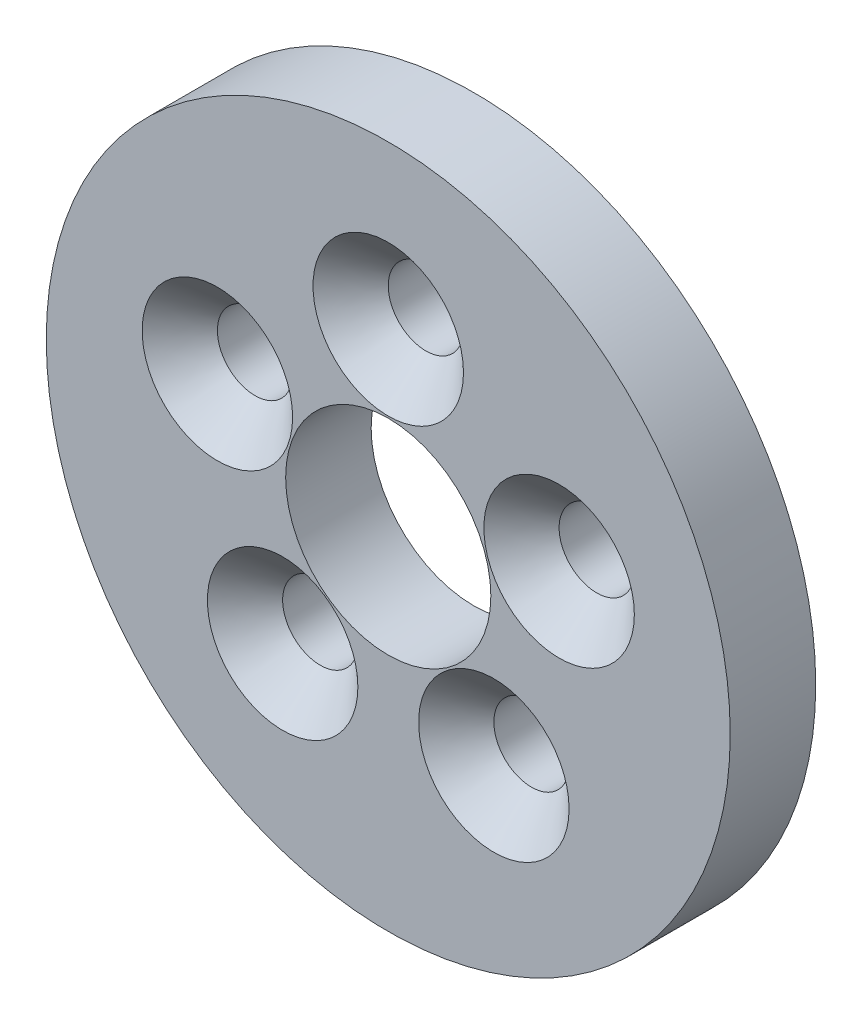
SolidWorks part; units mm, degrees
ref_plane "Front Plane" through (0, 0, 0) normal (0, 0, 1) x (1, 0, 0)
ref_plane "Top Plane" through (0, 0, 0) normal (0, 1, 0) x (1, 0, 0)
ref_plane "Right Plane" through (0, 0, 0) normal (1, 0, 0) x (0, 0, -1)
sketch "Sketch1" plane through (0, 0, 0) normal (0, 0, 1) x (1, 0, 0)
  line L1 (0, 5.2533) -> (-4.9962, 1.6234)
  line L2 (-4.9962, 1.6234) -> (-3.0878, -4.25)
  line L3 (-3.0878, -4.25) -> (3.0878, -4.25)
  line L4 (3.0878, -4.25) -> (4.9962, 1.6234)
  line L5 (4.9962, 1.6234) -> (0, 5.2533)
  circle A0 centre (0, 0) radius 10
  circle A1 centre (0, 0) radius 4.25 construction
  circle A2 centre (0, 0) radius 3
  dimension "D1" = 20
  dimension "D2" = 8.5
  dimension "D3" = 6
extrude "Boss-Extrude1" add sketch "Sketch1" along normal blind 2.5 contours A0 L5 L4 L3 L2 L1 | L4 L5 L1 L2 L3 A2
hole_wizard "CSK for M2 Flat Head Machine Screw3" positions "Sketch2" profile "Sketch3" countersink size "M2" standard "ANSI Metric" end condition up to next
sketch "Sketch2" plane through (0, 0, 2.5) normal (0, 0, 1) x (1, 0, 0)
  point P0 (0, 5.2533)
  point P3 (4.9962, 1.6234)
  point P6 (3.0878, -4.25)
  point P9 (-4.9962, 1.6234)
  point P12 (-3.0878, -4.25)
sketch "Sketch3" plane through (0, 5.2533, 2.5) normal (1, 0, 0) x (0, -1, 0)
  line L0 (0, 0) -> (0, 2.5)
  line L1 (0, 2.5) -> (1.1, 2.5)
  line L2 (1.1, 2.5) -> (1.1, 1.1)
  line L3 (1.1, 1.1) -> (2.2, 0)
  line L5 (2.2, 0) -> (0, 0)
  line L6 (-1.1, 1.1) -> (-2.2, 0) construction
  line L11 (0, -6.35) -> (0, 107.95) construction
  dimension "Thru Hole Dia." = 2.2
  dimension "Thru Hole Depth" = 2.5
  dimension "Near C'Sink Dia." = 4.4
  dimension "Near C'Sink Angle" = 90
